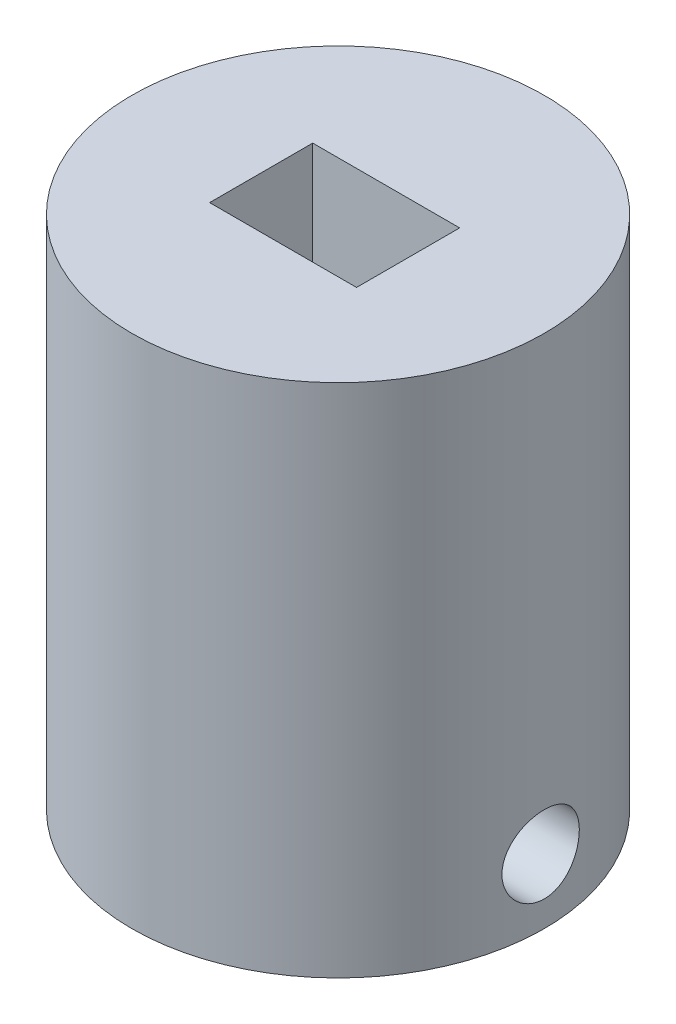
SolidWorks part; units mm, degrees
ref_plane "Front Plane" through (0, 0, 0) normal (0, 0, 1) x (1, 0, 0)
ref_plane "Top Plane" through (0, 0, 0) normal (0, 1, 0) x (1, 0, 0)
ref_plane "Right Plane" through (0, 0, 0) normal (1, 0, 0) x (0, 0, -1)
sketch "Sketch3" plane through (0, 0, 0) normal (0, 1, 0) x (1, 0, 0)
  circle A0 centre (0, 0) radius 8
  dimension "D1" = 16
extrude "Boss-Extrude1" add sketch "Sketch3" along normal blind 20
sketch "Sketch4" plane through (0, 0, 0) normal (0, -1, 0) x (1, 0, 0)
  circle A0 centre (0, 0) radius 4
  dimension "D1" = 8
extrude "Cut-Extrude1" cut sketch "Sketch4" against normal blind 12
sketch "Sketch5" plane through (0, 0, 0) normal (1, 0, 0) x (0, 0, -1)
  circle A0 centre (0, 2.5) radius 1.5
  dimension "D1" = 3
  dimension "D2" = 2.5
extrude "Cut-Extrude2" cut sketch "Sketch5" against normal through all both and the other way through all
sketch "Sketch6" plane through (0, 20, 0) normal (0, 1, 0) x (1, 0, 0)
  line L0 (0, 0) -> (-2.8844, 0) construction
  line L1 (0, 0) -> (0, 8) construction
  line L2 (-2.8844, 1.9018) -> (2.8156, 1.9018)
  line L3 (-2.8844, 1.9018) -> (-2.8844, -2.0982)
  line L4 (-2.8844, -2.0982) -> (2.8156, -2.0982)
  line L5 (2.8156, 1.9018) -> (2.8156, -2.0982)
  line L6 (0, 0) -> (-8, 0) construction
  circle A0 centre (0, 0) radius 8 construction
  dimension "D1" = 5.7
  dimension "D2" = 4
  dimension "D3" = 8
  dimension "D4" = 8
extrude "Cut-Extrude3" cut sketch "Sketch6" against normal blind 6
